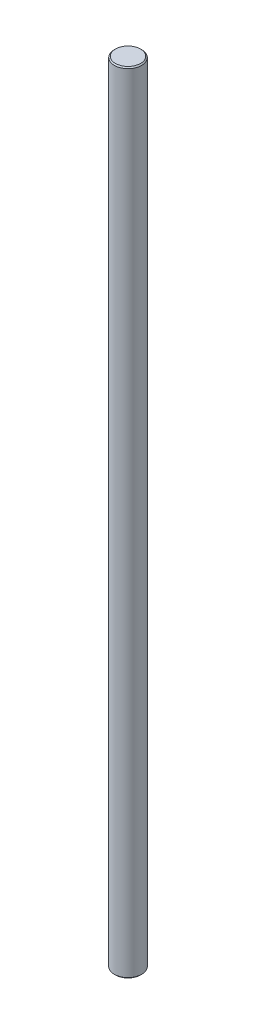
SolidWorks part; units mm, degrees
ref_plane "Alzado" through (0, 0, 0) normal (0, 0, 1) x (1, 0, 0)
ref_plane "Planta" through (0, 0, 0) normal (0, 1, 0) x (1, 0, 0)
ref_plane "Vista lateral" through (0, 0, 0) normal (1, 0, 0) x (0, 0, -1)
sketch "Croquis1" plane through (0, -32.9118, 0) normal (0, 1, 0) x (1, 0, 0)
  circle A0 centre (-109.0288, -1.2744) radius 6
  dimension "D1" = 12
extrude "Saliente-Extruir1" add sketch "Croquis1" along normal up to surface (346.5 mm away)
chamfer "Chaflán1" distance 0.5 angle 45 2 edges at (-109.0288, 313.5882, 7.2744) (-109.0288, -32.9118, 7.2744)
